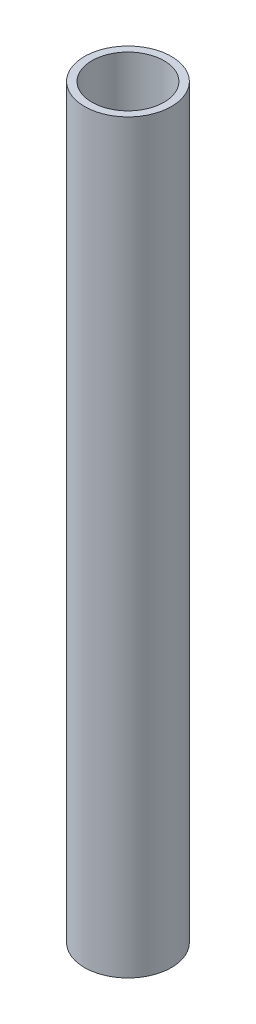
SolidWorks part; units mm, degrees
material "6061 Alloy"
ref_plane "Front Plane" through (0, 0, 0) normal (0, 0, 1) x (1, 0, 0)
ref_plane "Top Plane" through (0, 0, 0) normal (0, 1, 0) x (1, 0, 0)
ref_plane "Right Plane" through (0, 0, 0) normal (1, 0, 0) x (0, 0, -1)
sketch "Sketch1" plane through (0, 0, 0) normal (0, 1, 0) x (1, 0, 0)
  circle A0 centre (0, 0) radius 21.082
  circle A1 centre (0, 0) radius 17.5006
  dimension "D1" = 42.164
  dimension "D2" = 35.0012
extrude "Boss-Extrude1" add sketch "Sketch1" along normal blind 361.95
